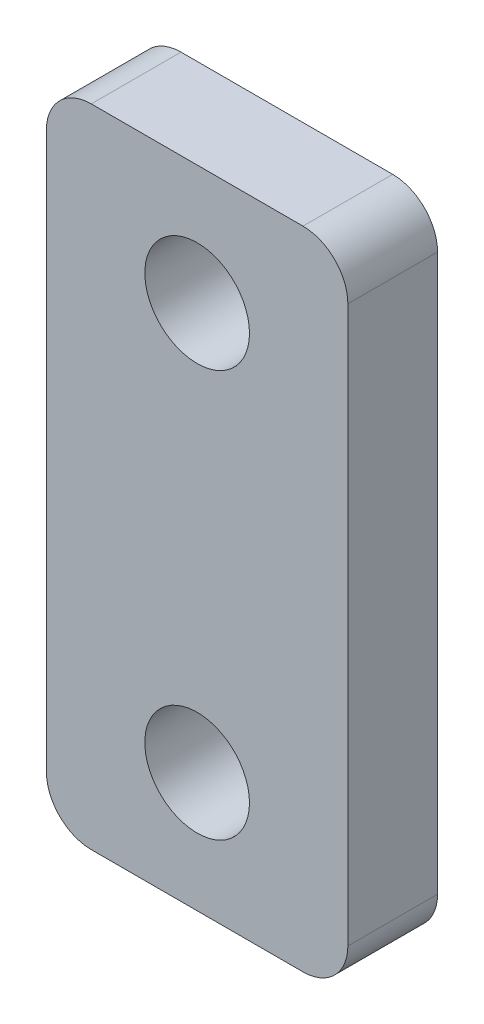
SolidWorks part; units mm, degrees
ref_plane "Front Plane" through (0, 0, 0) normal (0, 0, 1) x (1, 0, 0)
ref_plane "Top Plane" through (0, 0, 0) normal (0, 1, 0) x (1, 0, 0)
ref_plane "Right Plane" through (0, 0, 0) normal (1, 0, 0) x (0, 0, -1)
sketch "Sketch1" plane through (0, 0, 0) normal (0, 0, 1) x (1, 0, 0)
  line L1 (-7.0798, -21.5996) -> (7.0798, -21.5996)
  line L2 (-10.0798, -18.5996) -> (-10.0798, 18.5996)
  line L3 (-7.0798, 21.5996) -> (7.0798, 21.5996)
  line L4 (10.0798, -18.5996) -> (10.0798, 18.5996)
  line L5 (-10.0798, -21.5996) -> (10.0798, 21.5996) construction
  line L6 (-10.0798, 21.5996) -> (10.0798, -21.5996) construction
  circle A0 centre (0, 13.5996) radius 3.5
  circle A1 centre (0, -13.5996) radius 3.5
  arc A2 (7.0798, -21.5996) -> (10.0798, -18.5996) centre (7.0798, -18.5996) ccw
  arc A3 (7.0798, 21.5996) -> (10.0798, 18.5996) centre (7.0798, 18.5996) cw
  arc A4 (-10.0798, 18.5996) -> (-7.0798, 21.5996) centre (-7.0798, 18.5996) cw
  arc A5 (-7.0798, -21.5996) -> (-10.0798, -18.5996) centre (-7.0798, -18.5996) cw
  point P0 (0, 0)
  dimension "D1" = 7
  dimension "D2" = 3
  dimension "D3" = 10.0798
  dimension "D4" = 13.5996
  dimension "D5" = 21.5996
  dimension "D6" = 13.5996
extrude "Boss-Extrude1" add sketch "Sketch1" along normal mid plane 6
